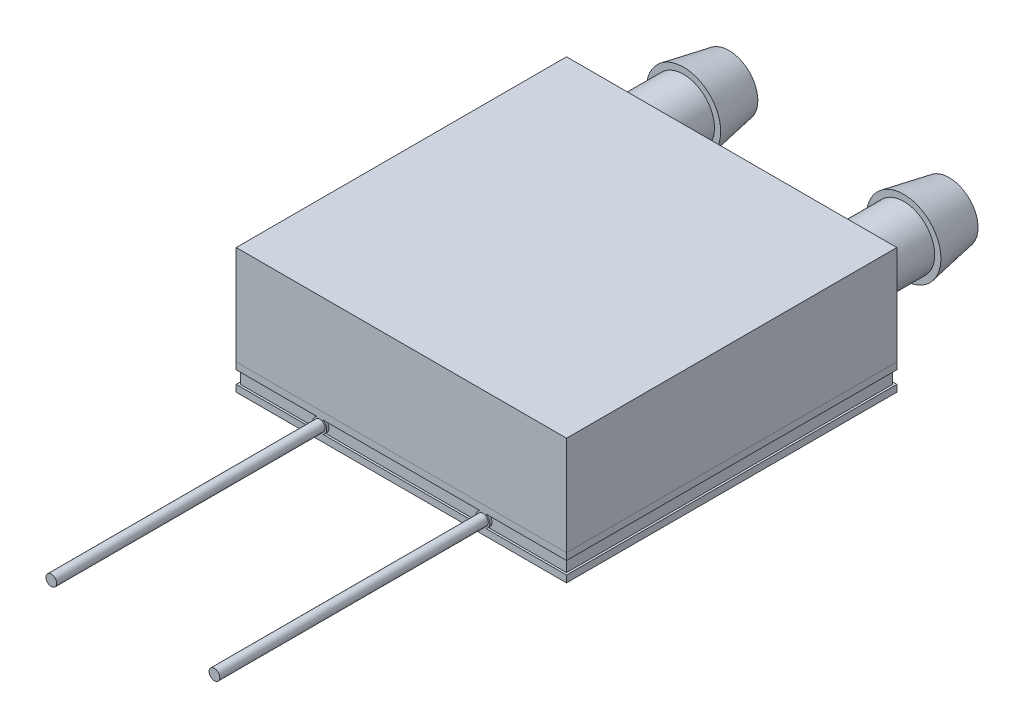
SolidWorks part; units mm, degrees
ref_plane "Front Plane" through (0, 0, 0) normal (0, 0, 1) x (1, 0, 0)
ref_plane "Top Plane" through (0, 0, 0) normal (0, 1, 0) x (1, 0, 0)
ref_plane "Right Plane" through (0, 0, 0) normal (1, 0, 0) x (0, 0, -1)
sketch "Sketch1" plane through (0, 0, 0) normal (0, 1, 0) x (1, 0, 0)
  line L1 (0, 0) -> (40, 0)
  line L2 (0, 0) -> (0, 40)
  line L3 (0, 40) -> (40, 40)
  line L4 (40, 0) -> (40, 40)
  dimension "D1" = 40
  dimension "D2" = 40
extrude "Boss-Extrude1" add sketch "Sketch1" along normal blind 3.175
ref_plane "Plane1" through (0, 1.5875, 0) normal (0, 1, 0) x (1, 0, 0)
sketch "Sketch2" plane through (0, 1.5875, 0) normal (0, 1, 0) x (1, 0, 0)
  line L0 (39.746, 39.746) -> (0.254, 39.746)
  line L1 (0.254, 39.746) -> (0.254, 0.254)
  line L2 (0.254, 0.254) -> (39.746, 0.254)
  line L3 (39.746, 0.254) -> (39.746, 39.746)
  line L4 (0, 40) -> (0, 0)
  line L5 (0, 0) -> (40, 0)
  line L6 (40, 0) -> (40, 40)
  line L7 (40, 40) -> (0, 40)
  line L8 (0, 40) -> (0, 0)
  line L9 (0, 0) -> (40, 0)
  line L10 (40, 0) -> (40, 40)
  line L11 (40, 40) -> (0, 40)
  dimension "D1" = 0
  dimension "D2" = 0.254
extrude "Cut-Extrude1" cut sketch "Sketch2" against normal blind 0.762 and the other way blind 0.762
sketch "Sketch3" plane through (0, 0, -0.254) normal (0, 0, 1) x (1, 0, 0)
  line L0 (20, 3.175) -> (20, 0)
  line L1 (0, 3.175) -> (40, 3.175) construction
  line L2 (0, 0) -> (40, 0) construction
  line L3 (20, 1.5875) -> (0.254, 1.5875)
  line L4 (0.254, 2.3495) -> (0.254, 0.8255) construction
  circle A0 centre (10.127, 1.5875) radius 0.8381
  circle A1 centre (29.873, 1.5875) radius 0.8381
extrude "Boss-Extrude2" add sketch "Sketch3" along normal blind 0.254 contours A1 | A0
sketch "Sketch4" plane through (0, 0, 0) normal (0, 0, 1) x (1, 0, 0)
  line L0 (20, 3.175) -> (20, 0)
  line L1 (0, 3.175) -> (40, 3.175) construction
  line L2 (0, 0) -> (40, 0) construction
  arc A0 (29.5241, 2.3495) -> (29.5241, 0.8255) centre (29.873, 1.5875) ccw construction
  arc A1 (10.4759, 0.8255) -> (10.4759, 2.3495) centre (10.127, 1.5875) ccw construction
  arc A2 (29.5241, 2.3495) -> (29.5241, 0.8255) centre (29.873, 1.5875) ccw
  arc A3 (10.4759, 0.8255) -> (10.4759, 2.3495) centre (10.127, 1.5875) ccw
  circle A4 centre (10.127, 1.5875) radius 0.6498
  circle A5 centre (29.873, 1.5875) radius 0.6498
extrude "Boss-Extrude3" add sketch "Sketch4" along normal blind 32.512 separate body contours A4 | A5
sketch "Sketch5" plane through (0, 3.175, 0) normal (0, 1, 0) x (1, 0, 0)
  line L4 (0, 40) -> (0, 0)
  line L5 (0, 0) -> (40, 0)
  line L6 (40, 0) -> (40, 40)
  line L7 (40, 40) -> (0, 40)
  line L8 (0, 40) -> (0, 0)
  line L9 (0, 0) -> (40, 0)
  line L10 (40, 0) -> (40, 40)
  line L11 (40, 40) -> (0, 40)
  dimension "D1" = 0
extrude "Boss-Extrude4" add sketch "Sketch5" along normal blind 12 separate body
ref_plane "Plane2" through (0, 9.175, 0) normal (0, 1, 0) x (1, 0, 0)
sketch "Sketch7" plane through (0, 9.175, 0) normal (0, 1, 0) x (1, 0, 0)
  line L0 (20, 40) -> (20, 0) construction
  line L1 (40, 40) -> (0, 40) construction
  line L2 (0, 0) -> (40, 0) construction
  line L3 (6.6667, 40) -> (6.6667, 6.6667)
  line L4 (6.6667, 6.6667) -> (15.5556, 6.6667)
  line L5 (15.5556, 6.6667) -> (15.5556, 33.3333)
  line L6 (15.5556, 33.3333) -> (24.4444, 33.3333)
  line L7 (0, 40) -> (0, 0) construction
  line L8 (33.3333, 6.6667) -> (24.4444, 6.6667)
  line L9 (33.3333, 40) -> (33.3333, 6.6667)
  line L10 (24.4444, 6.6667) -> (24.4444, 33.3333)
  point P17 (20, 33.3333)
  dimension "D1" = 6.6667
  dimension "D2" = 8.8889
  dimension "D3" = 6.6667
  dimension "D4" = 6.6667
sweep "Cut-Sweep1" cut path "Sketch7" circular profile diameter 6 parameters "D3"=6
sketch "Sketch16" plane through (0, 9.175, 0) normal (0, 1, 0) x (1, 0, 0)
  line L0 (9.6667, 40) -> (3.6667, 40) construction
  line L1 (9.6667, 40) -> (3.6667, 40)
  line L2 (9.6667, 40) -> (9.6667, 41)
  line L3 (6.6667, 40) -> (11.1667, 40)
  line L4 (40, 40) -> (0, 40) construction
  line L5 (11.1667, 40) -> (11.1667, 41)
  line L6 (11.1667, 41) -> (9.6667, 41)
  line L7 (6.6667, 40) -> (6.6667, 53)
  line L8 (9.6667, 41) -> (9.6667, 47.5)
  line L9 (9.6667, 47.5) -> (11.1667, 47.5)
  line L10 (6.6667, 53) -> (10.1667, 53)
  line L11 (9.6667, 40) -> (9.6667, 53)
  line L12 (10.1667, 53) -> (11.1667, 47.5)
  line L13 (10.4167, 47.5) -> (10.4167, 41)
  dimension "D1" = 4.5
  dimension "D2" = 1
  dimension "D3" = 13
  dimension "D4" = 6.5
  dimension "D5" = 1.5
  dimension "D6" = 3.5
revolve "Revolve1" add sketch "Sketch16" angle 360 about L7
ref_plane "Plane3" through (20, 0, 0) normal (1, 0, 0) x (0, 0, -1)
mirror "Mirror1" about plane through (20, 0, 0) normal (1, 0, 0) of "Revolve1"
equation "\"D2@Sketch7\"=(40mm - \"D1@Sketch7\"*2)/3"
equation "\"D3@Sketch7\"=\"D1@Sketch7\""
equation "\"D4@Sketch7\"=\"D1@Sketch7\""
